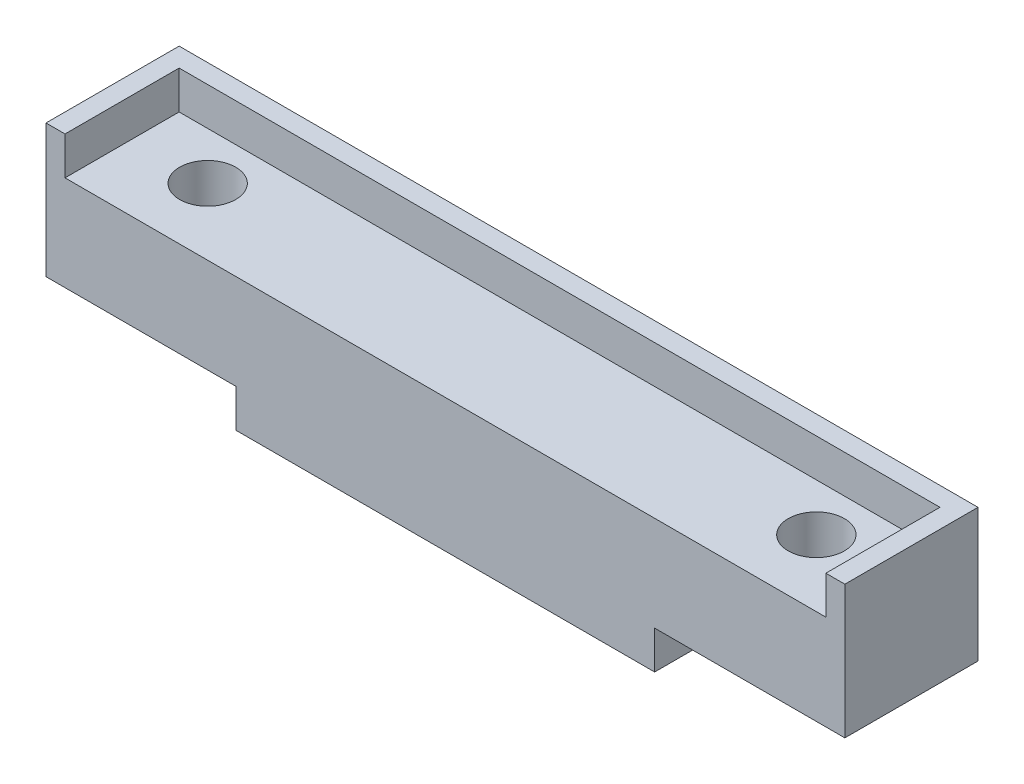
SolidWorks part; units mm, degrees
ref_plane "Front Plane" through (0, 0, 0) normal (0, 0, 1) x (1, 0, 0)
ref_plane "Top Plane" through (0, 0, 0) normal (0, 1, 0) x (1, 0, 0)
ref_plane "Right Plane" through (0, 0, 0) normal (1, 0, 0) x (0, 0, -1)
sketch "Sketch1" plane through (0, 0, 0) normal (0, 1, 0) x (1, 0, 0)
  line L1 (0, 7) -> (42, 7)
  line L2 (0, 7) -> (0, 0)
  line L3 (0, 0) -> (42, 0)
  line L4 (42, 7) -> (42, 0)
  dimension "D1" = 7
  dimension "D2" = 42
extrude "Riser" add sketch "Sketch1" along normal blind 7
sketch "Sketch2" plane through (0, 0, 0) normal (0, -1, 0) x (1, 0, 0)
  line L0 (0, -7) -> (0, 0) construction
  line L1 (21, 0) -> (21, -7) construction
  line L2 (0, 0) -> (42, 0) construction
  line L3 (42, -7) -> (0, -7) construction
  circle A0 centre (5, -3.5) radius 1.475
  circle A1 centre (37, -3.5) radius 1.475
  point P6 (0, -3.5)
  dimension "D2" = 2.95
  dimension "D1" = 5
extrude "Mounting Holes" cut sketch "Sketch2" against normal through all
sketch "Sketch3" plane through (0, 7, 0) normal (0, 1, 0) x (1, 0, 0)
  line L0 (41, 6) -> (1, 6)
  line L1 (1, 6) -> (1, 1)
  line L2 (1, 1) -> (41, 1)
  line L3 (41, 1) -> (41, 6)
  line L4 (0, 7) -> (0, 0)
  line L5 (0, 0) -> (42, 0)
  line L6 (42, 0) -> (42, 7)
  line L7 (42, 7) -> (0, 7)
  line L8 (0, 7) -> (0, 0)
  line L9 (0, 0) -> (42, 0)
  line L10 (42, 0) -> (42, 7)
  line L11 (42, 7) -> (0, 7)
  dimension "D1" = 0
  dimension "D2" = 1
extrude "Recess (4-Sides)" [suppressed] cut sketch "Sketch3" against normal blind 2 contours L0 L1 L2 L3
sketch "Sketch4" plane through (0, 7, 0) normal (0, 1, 0) x (1, 0, 0)
  line L0 (0, 0) -> (42, 0) construction
  line L1 (1, 6) -> (41, 6)
  line L2 (1, 6) -> (1, 0)
  line L3 (1, 0) -> (41, 0)
  line L4 (41, 6) -> (41, 0)
  line L5 (0, 7) -> (0, 0) construction
  line L6 (42, 0) -> (42, 7) construction
  line L7 (42, 7) -> (0, 7) construction
  dimension "D1" = 1
  dimension "D2" = 1
  dimension "D3" = 1
extrude "Recess (3-Sides)" cut sketch "Sketch4" against normal blind 2
sketch "Sketch5" plane through (0, 0, 0) normal (0, -1, 0) x (1, 0, 0)
  line L1 (10, 0) -> (32, 0)
  line L2 (10, 0) -> (10, -7)
  line L3 (10, -7) -> (32, -7)
  line L4 (32, 0) -> (32, -7)
  point P4 (37, -3.5)
  point P5 (5, -3.5)
  point P6 (10, -3.5)
  point P9 (32, -3.5)
  dimension "D1" = 5
  dimension "D2" = 5
  dimension "D3" = 7
extrude "Alignment Tab" add sketch "Sketch5" along normal blind 2
